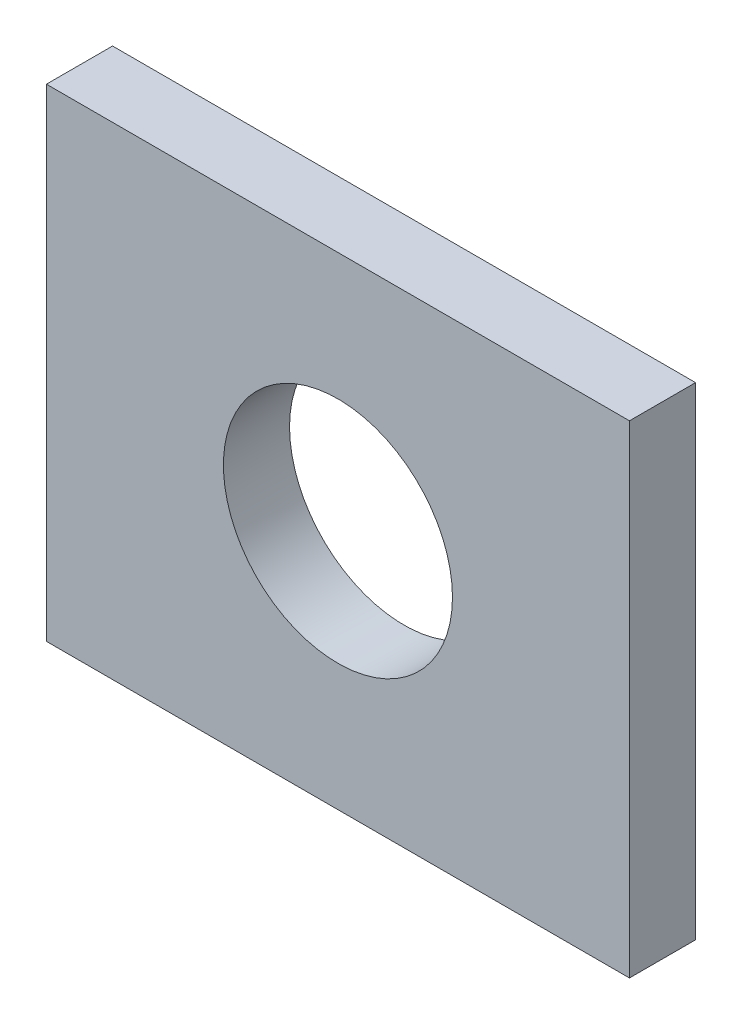
SolidWorks part; units mm, degrees
ref_plane "Front Plane" through (0, 0, 0) normal (0, 0, 1) x (1, 0, 0)
ref_plane "Top Plane" through (0, 0, 0) normal (0, 1, 0) x (1, 0, 0)
ref_plane "Right Plane" through (0, 0, 0) normal (1, 0, 0) x (0, 0, -1)
sketch "Sketch1" plane through (0, 0, 0) normal (0, 0, 1) x (1, 0, 0)
  line L1 (-6.35, -6.35) -> (49.65, -6.35)
  line L2 (-6.35, -6.35) -> (-6.35, 40)
  line L3 (-6.35, 40) -> (49.65, 40)
  line L4 (49.65, -6.35) -> (49.65, 40)
extrude "Boss-Extrude1" add sketch "Sketch1" along normal blind 6.35
sketch "Sketch3" plane through (0, 0, 6.35) normal (0, 0, 1) x (1, 0, 0)
  line L0 (21.65, -6.35) -> (21.65, 40) construction
  line L1 (-6.35, -6.35) -> (49.65, -6.35) construction
  line L2 (49.65, 40) -> (-6.35, 40) construction
  line L3 (49.65, 16.825) -> (-6.35, 16.825) construction
  line L4 (49.65, -6.35) -> (49.65, 40) construction
  line L5 (-6.35, 40) -> (-6.35, -6.35) construction
  circle A0 centre (21.65, 16.825) radius 11
extrude "Cut-Extrude1" cut sketch "Sketch3" against normal up to next
